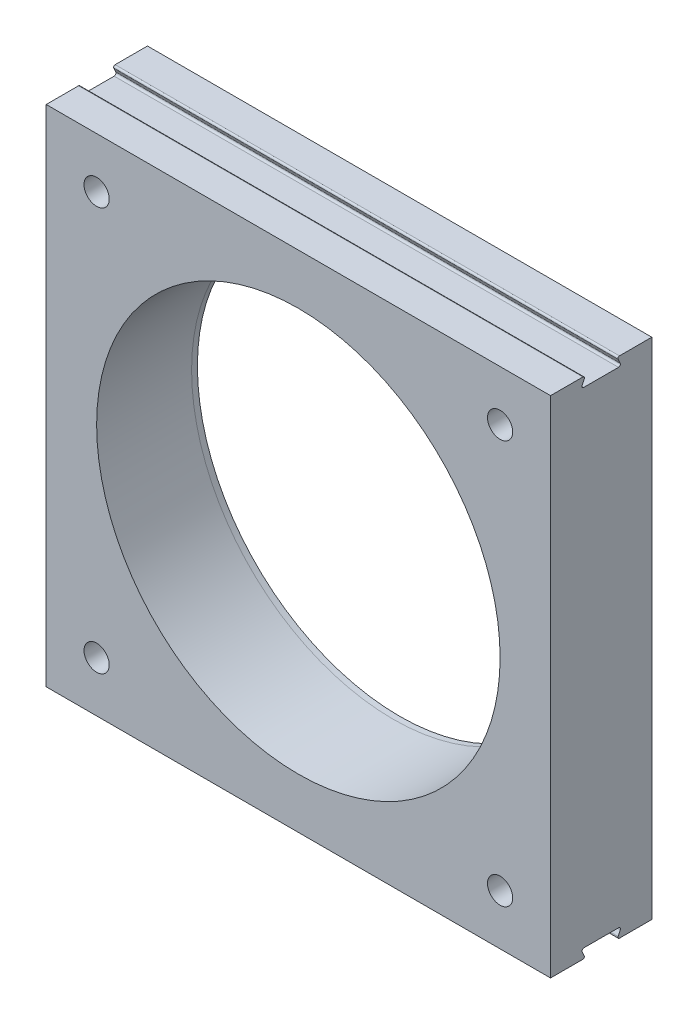
SolidWorks part; units mm, degrees
material "PW60:2:C1:0:1:2:Re:26:"
ref_plane "Plane1" through (0, 0, 0) normal (0, 0, 1) x (1, 0, 0)
ref_plane "Plane2" through (0, 0, 0) normal (0, 1, 0) x (1, 0, 0)
ref_plane "Plane3" through (0, 0, 0) normal (1, 0, 0) x (0, 0, -1)
sketch "Sketch1" plane through (0, 0, 0) normal (0, 0, 1) x (1, 0, 0)
  line L0 (-127, 127) -> (127, 127)
  line L1 (-127, 127) -> (-127, -127)
  line L2 (127, -127) -> (-127, -127)
  line L3 (127, -127) -> (127, 127)
  dimension "Length" = 254
  dimension "D2" = 127
  dimension "Width" = 254
  dimension "D4" = 127
extrude "Base-Extrude" add sketch "Sketch1" along normal mid plane 51
sketch "Sketch2" plane through (127, 0, 0) normal (1, 0, 0) x (0, 0, -1)
  line L0 (-7.9375, 127) -> (7.9375, 127)
  line L1 (8.7313, 122.2375) -> (-8.7312, 122.2375)
  line L4 (-25.5, 127) -> (25.5, 127) construction
  line L5 (0, 127) -> (0, 111.4524) construction
  line L6 (7.9375, 127) -> (9.5904, 123.6127)
  line L7 (-7.9375, 127) -> (-9.5904, 123.6127)
  arc A0 (9.5904, 123.6127) -> (8.7313, 122.2375) centre (8.7313, 123.1935) cw
  arc A1 (-9.5904, 123.6127) -> (-8.7312, 122.2375) centre (-8.7312, 123.1935) ccw
  point P6 (0, 127)
  dimension "D1" = 15.875
  dimension "D2" = 4.7625
  dimension "D3" = 17.4625
sketch "Sketch3" plane through (0, 0, 0) normal (0, 0, 1) x (1, 0, 0)
  line L4 (-127, 127) -> (-127, -127)
  line L5 (-127, -127) -> (127, -127)
  line L6 (127, -127) -> (127, 127)
  line L7 (127, 127) -> (-127, 127)
  line L11 (127, 127) -> (-127, 127)
  dimension "D1" = 0
sweep "Cut-Sweep1" cut profiles "Sketch2" path "Sketch3"
fillet "Fillet4" radius 0.7937 2 edges at (0, 127, 7.9375) (0, 127, -7.9375)
mirror "Mirror3" about plane through (0, 0, 0) normal (0, 1, 0) of "Fillet4", "Cut-Sweep1"
sketch "Sketch4" plane through (0, 0, 25.5) normal (0, 0, 1) x (1, 0, 0)
  line L1 (-127, 127) -> (127, 127) construction
  line L2 (-127, 127) -> (-127, -127) construction
  circle A0 centre (-101.6, 101.6) radius 6.35
  dimension "D1" = 25.4
  dimension "D3" = 12.7
  dimension "D2" = 25.4
extrude "Cut-Extrude1" cut sketch "Sketch4" against normal through all
mirror "Mirror1" about plane through (0, 0, 0) normal (0, 1, 0) of "Cut-Extrude1"
mirror "Mirror2" about plane through (0, 0, 0) normal (1, 0, 0) of "Cut-Extrude1", "Mirror1"
sketch "Sketch5" plane through (0, 0, -25.5) normal (0, 0, -1) x (-1, 0, 0)
  circle A0 centre (0, 0) radius 101.85
  circle A1 centre (0, 0) radius 101.6
  dimension "D1" = 203.7
  dimension "Diameter" = 203.2
extrude "Cut-Extrude2" cut sketch "Sketch5" against normal blind 3.175
sketch "Sketch7" plane through (0, 0, -25.5) normal (0, 0, -1) x (-1, 0, 0)
  circle A1 centre (0, 0) radius 101.6
  circle A2 centre (0, 0) radius 101.6
  dimension "D1" = 0
extrude "Cut-Extrude3" cut sketch "Sketch7" against normal through all
equation "\"D2@Sketch1\" = \"Length@Sketch1\"/2"
equation "\"D4@Sketch1\" = \"Width@Sketch1\"/2"
equation "\"D1@Sketch5\" = \"Diameter@Sketch5\"+.5"
